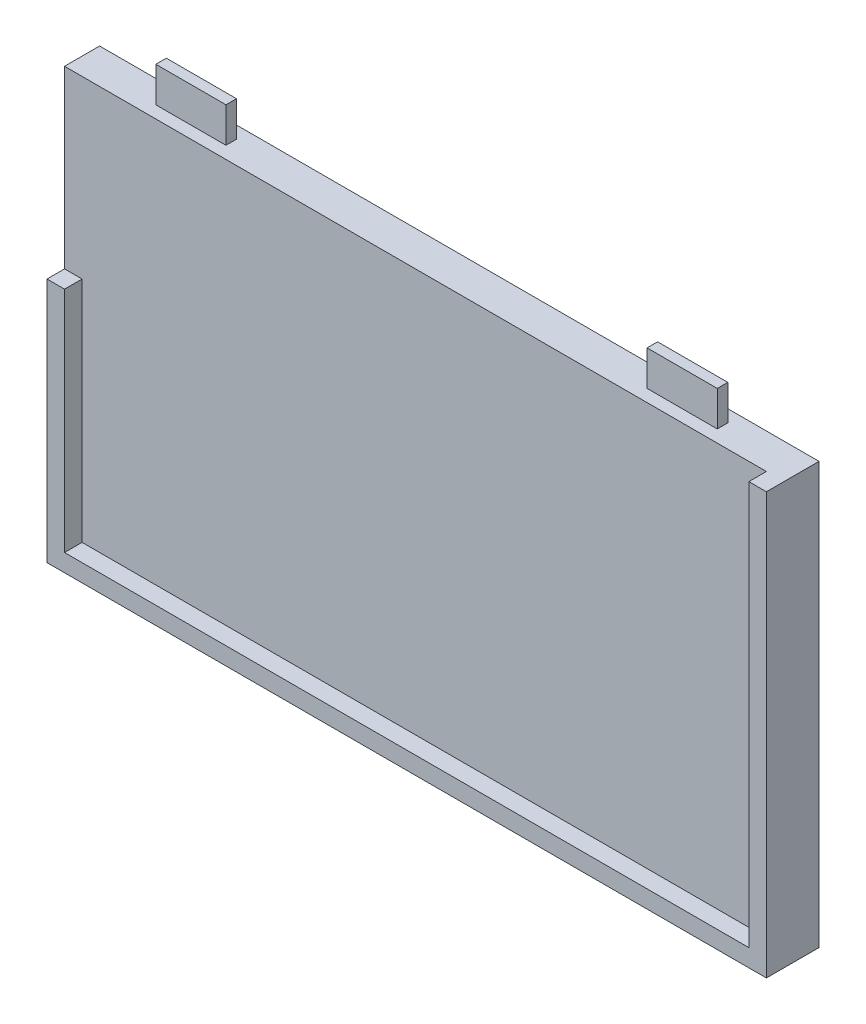
SolidWorks part; units mm, degrees
ref_plane "Front Plane" through (0, 0, 0) normal (1, 0, 0) x (0, 1, 0)
ref_plane "Top Plane" through (0, 0, 0) normal (0, 0, 1) x (0, 1, 0)
ref_plane "Right Plane" through (0, 0, 0) normal (0, 1, 0) x (-1, 0, 0)
sketch "Sketch1" plane through (0, 0, 0) normal (0, 0, 1) x (0, 1, 0)
  line L1 (-60, -102.5) -> (60, -102.5)
  line L2 (-60, -102.5) -> (-60, 102.5)
  line L3 (-60, 102.5) -> (60, 102.5)
  line L4 (60, -102.5) -> (60, 102.5)
  line L5 (-60, -102.5) -> (60, 102.5) construction
  line L6 (-60, 102.5) -> (60, -102.5) construction
  point P0 (0, 0)
  dimension "D1" = 205
  dimension "D2" = 120
extrude "Boss-Extrude1" add sketch "Sketch1" along normal blind 10
sketch "Sketch2" plane through (0, 0, 10) normal (0, 0, 1) x (1, 0, 0)
  line L1 (102.5, 60) -> (-102.5, 60) construction
  line L3 (-97.5, -55) -> (97.5, -55)
  line L4 (97.5, -55) -> (97.5, 60)
  line L5 (97.5, 60) -> (102.5, 60)
  line L6 (102.5, 60) -> (102.5, -60)
  line L7 (102.5, -60) -> (-102.5, -60)
  line L8 (-102.5, 60) -> (-102.5, -60) construction
  line L9 (-102.5, -60) -> (-102.5, 10)
  line L10 (-97.5, -55) -> (-97.5, 10)
  line L12 (-102.5, 10) -> (-97.5, 10)
  dimension "D1" = 5
  dimension "D2" = 5
  dimension "D3" = 5
  dimension "D4" = 50
extrude "Boss-Extrude2" add sketch "Sketch2" along normal blind 5
sketch "Sketch3" plane through (-102.5, 0, 0) normal (-1, 0, 0) x (0, -1, 0)
  line L0 (-60, 0) -> (60, 0) construction
  line L1 (-40.25, 3.4) -> (-19.75, 3.4)
  line L2 (-40.25, 3.4) -> (-40.25, 6.6)
  line L3 (-40.25, 6.6) -> (-19.75, 6.6)
  line L4 (-19.75, 3.4) -> (-19.75, 6.6)
  line L5 (-40.25, 3.4) -> (-19.75, 6.6) construction
  line L6 (-40.25, 6.6) -> (-19.75, 3.4) construction
  line L7 (-60, 10) -> (-60, 0) construction
  point P0 (-30, 5)
  dimension "D1" = 5
  dimension "D2" = 3.2
  dimension "D3" = 20.5
  dimension "D4" = 30
extrude "Cut-Extrude1" cut sketch "Sketch3" against normal blind 10
sketch "Sketch4" plane through (0, 60, 0) normal (0, 1, 0) x (-1, 0, 0)
  line L0 (0, -1000) -> (0, 49000) construction
  line L1 (-102.5, 0) -> (102.5, 0) construction
  line L2 (-60, 6.5) -> (-80, 3.5) construction
  line L3 (60, 3.5) -> (80, 3.5)
  line L4 (60, 3.5) -> (60, 6.5)
  line L5 (60, 6.5) -> (80, 6.5)
  line L6 (80, 3.5) -> (80, 6.5)
  line L7 (60, 3.5) -> (80, 6.5) construction
  line L8 (60, 6.5) -> (80, 3.5) construction
  line L9 (-60, 3.5) -> (-80, 6.5) construction
  line L10 (-80, 3.5) -> (-80, 6.5)
  line L11 (-60, 6.5) -> (-80, 6.5)
  line L12 (-60, 3.5) -> (-60, 6.5)
  line L13 (-60, 3.5) -> (-80, 3.5)
  point P1 (70, 5)
  point P5 (0, 0)
  point P14 (-70, 5)
  dimension "D1" = 3
  dimension "D2" = 20
  dimension "D3" = 5
  dimension "D4" = 70
extrude "Boss-Extrude3" add sketch "Sketch4" along normal blind 10
sketch "Sketch5" plane through (0, -60, 0) normal (0, -1, 0) x (1, 0, 0)
  line L1 (12.4, 0) -> (17.6, 0)
  line L2 (12.4, 0) -> (12.4, 3.2)
  line L3 (12.4, 3.2) -> (17.6, 3.2)
  line L4 (17.6, 0) -> (17.6, 3.2)
  line L5 (12.4, 0) -> (17.6, 3.2) construction
  line L6 (12.4, 3.2) -> (17.6, 0) construction
  line L8 (-102.5, 0) -> (102.5, 0) construction
  line L9 (-17.6, 0) -> (-12.4, 0)
  line L10 (-17.6, 0) -> (-17.6, 3.2)
  line L11 (-17.6, 3.2) -> (-12.4, 3.2)
  line L12 (-12.4, 0) -> (-12.4, 3.2)
  line L13 (-17.6, 0) -> (-12.4, 3.2) construction
  line L14 (-17.6, 3.2) -> (-12.4, 0) construction
  point P0 (15, 1.6)
  point P11 (-15, 1.6)
  dimension "D1" = 2
  dimension "D2" = 5.2
  dimension "D3" = 3.2
  dimension "D4" = 15
  dimension "D5" = 30
extrude "Cut-Extrude2" cut sketch "Sketch5" against normal blind 5
